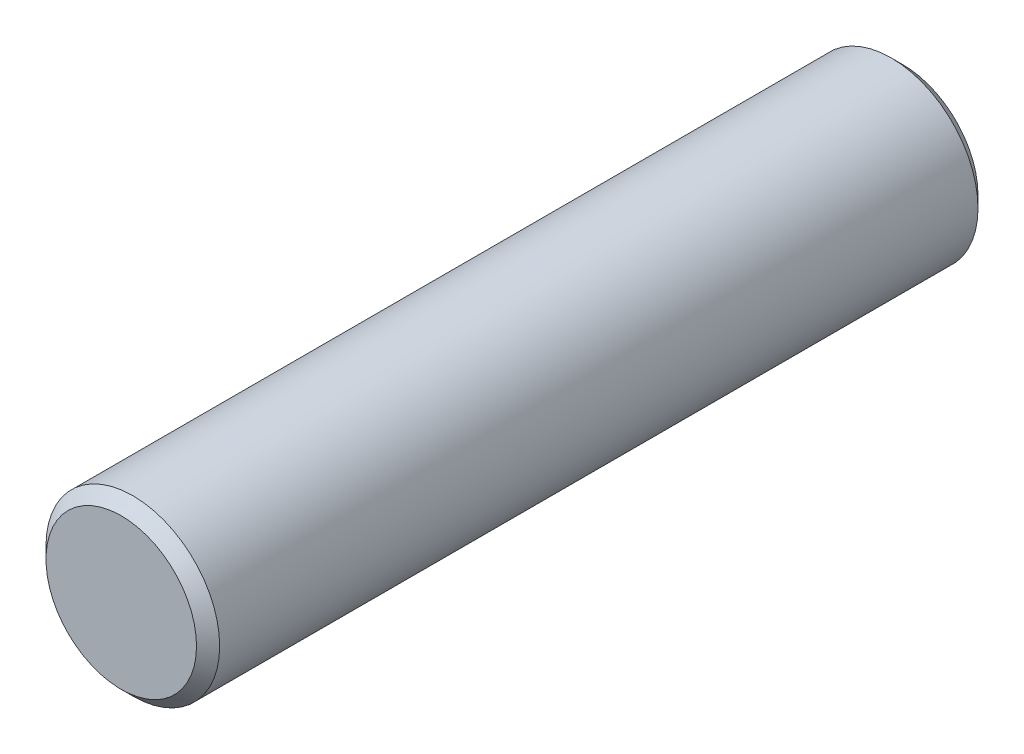
SolidWorks part; units mm, degrees
ref_plane "Front Plane" through (0, 0, 0) normal (0, 0, 1) x (1, 0, 0)
ref_plane "Top Plane" through (0, 0, 0) normal (0, 1, 0) x (1, 0, 0)
ref_plane "Right Plane" through (0, 0, 0) normal (1, 0, 0) x (0, 0, -1)
sketch "Sketch1" plane through (0, 0, 0) normal (0, 0, 1) x (1, 0, 0)
  circle A0 centre (0, 0) radius 1.5
extrude "Boss-Extrude1" add sketch "Sketch1" along normal mid plane 13.5
chamfer "Chamfer1" distance 0.2 angle 45 2 edges at (1.5, 0, -6.75) (1.5, 0, 6.75)
